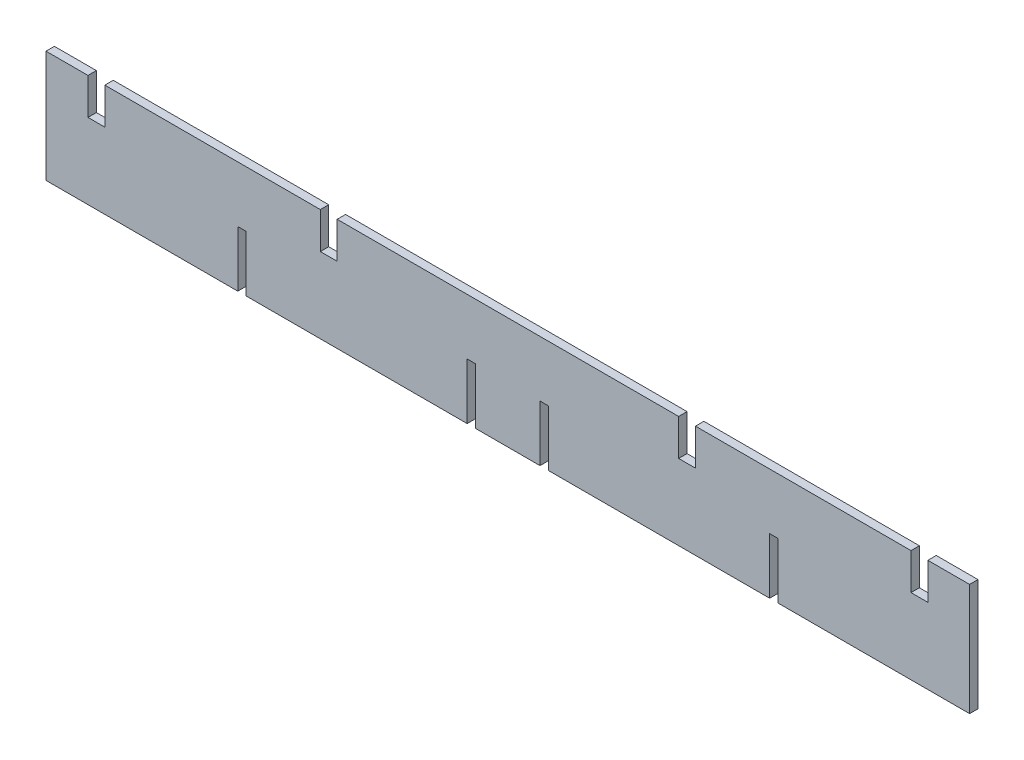
SolidWorks part; units mm, degrees
ref_plane "Front Plane" through (0, 0, 0) normal (0, 0, 1) x (1, 0, 0)
ref_plane "Top Plane" through (0, 0, 0) normal (0, 1, 0) x (1, 0, 0)
ref_plane "Right Plane" through (0, 0, 0) normal (1, 0, 0) x (0, 0, -1)
sketch "Sketch1" plane through (0, 0, 0) normal (0, 0, 1) x (1, 0, 0)
  line L1 (-330, 40) -> (330, 40)
  line L2 (-330, 40) -> (-330, -40)
  line L3 (-330, -40) -> (330, -40)
  line L4 (330, 40) -> (330, -40)
  line L5 (-330, 40) -> (330, -40) construction
  line L6 (-330, -40) -> (330, 40) construction
  point P0 (0, 0)
  dimension "D1" = 660
  dimension "D2" = 80
extrude "Boss-Extrude1" add sketch "Sketch1" along normal blind 6
sketch "Sketch2" plane through (0, 0, 6) normal (0, 0, 1) x (1, 0, 0)
  line L0 (-300, 40) -> (-300, 14)
  line L1 (330, 40) -> (-330, 40) construction
  line L2 (-300, 14) -> (-287.96, 14)
  line L3 (-287.96, 14) -> (-287.96, 40)
  line L4 (-287.96, 40) -> (-300, 40)
  line L5 (-330, 40) -> (-330, -40) construction
  line L6 (-133.96, 40) -> (-121.92, 40)
  line L7 (-133.96, 40) -> (-133.96, 14)
  line L8 (-133.96, 14) -> (-121.92, 14)
  line L9 (-121.92, 40) -> (-121.92, 14)
  line L10 (122.08, 40) -> (134.12, 40)
  line L11 (122.08, 40) -> (122.08, 14)
  line L12 (122.08, 14) -> (134.12, 14)
  line L13 (134.12, 40) -> (134.12, 14)
  line L14 (288.12, 40) -> (300.16, 40)
  line L15 (288.12, 40) -> (288.12, 14)
  line L16 (288.12, 14) -> (300.16, 14)
  line L17 (300.16, 40) -> (300.16, 14)
  dimension "D1" = 26
  dimension "D2" = 26
  dimension "D3" = 26
  dimension "D4" = 26
  dimension "D5" = 12.04
  dimension "D6" = 12.04
  dimension "D7" = 12.04
  dimension "D8" = 12.04
  dimension "D9" = 30
  dimension "D10" = 154
  dimension "D11" = 244
  dimension "D12" = 154
extrude "Cut-Extrude1" cut sketch "Sketch2" against normal through all
sketch "Sketch3" plane through (0, 0, 6) normal (0, 0, 1) x (1, 0, 0)
  line L3 (-29.04, 0) -> (-23, 0)
  line L8 (23, 0) -> (29.04, 0)
  line L12 (-29.04, 0) -> (-29.04, -40)
  line L13 (-330, -40) -> (330, -40) construction
  line L14 (-29.04, -40) -> (-23, -40)
  line L15 (-23, -40) -> (-23, 0)
  line L16 (23, 0) -> (23, -40)
  line L17 (23, -40) -> (29.04, -40)
  line L18 (29.04, -40) -> (29.04, 0)
  line L20 (0, 0) -> (0, 62.834) construction
  dimension "D1" = 6.04
  dimension "D2" = 6.04
  dimension "D3" = 40
  dimension "D4" = 40
  dimension "D5" = 23
  dimension "D6" = 23
extrude "Cut-Extrude2" cut sketch "Sketch3" against normal through all
sketch "Sketch4" plane through (0, 0, 6) normal (0, 0, 1) x (1, 0, 0)
  line L0 (-330, -40) -> (-29.04, -40) construction
  line L1 (-186.96, -40) -> (-192.96, -40)
  line L2 (-186.96, -40) -> (-186.96, 0)
  line L3 (-186.96, 0) -> (-192.96, 0)
  line L4 (-192.96, -40) -> (-192.96, 0)
  line L5 (29.04, -40) -> (330, -40) construction
  line L6 (193.12, -40) -> (187.12, -40)
  line L7 (193.12, -40) -> (193.12, 0)
  line L8 (193.12, 0) -> (187.12, 0)
  line L9 (187.12, -40) -> (187.12, 0)
  line L10 (-287.96, 14) -> (-287.96, 40) construction
  line L11 (288.12, 40) -> (288.12, 14) construction
  dimension "D1" = 6
  dimension "D2" = 40
  dimension "D3" = 95
  dimension "D4" = 40
  dimension "D5" = 6
  dimension "D6" = 95
extrude "Cut-Extrude3" cut sketch "Sketch4" against normal up to next
